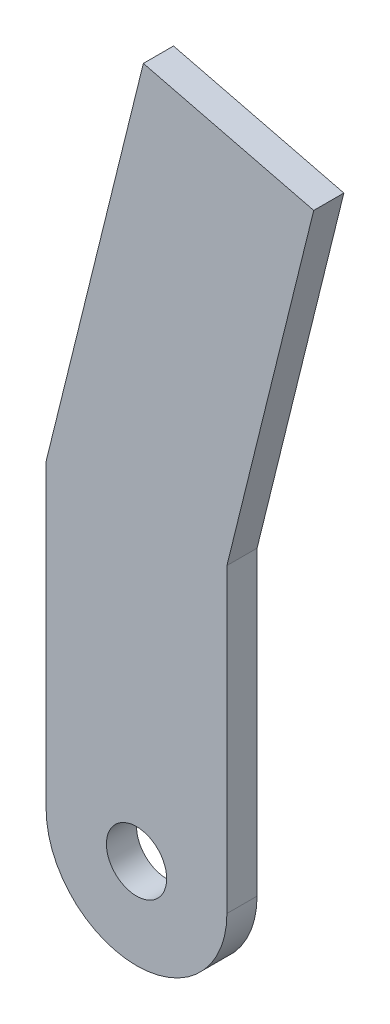
SolidWorks part; units mm, degrees
ref_plane "Front Plane" through (0, 0, 0) normal (0, 0, 1) x (1, 0, 0)
ref_plane "Top Plane" through (0, 0, 0) normal (0, 1, 0) x (1, 0, 0)
ref_plane "Right Plane" through (0, 0, 0) normal (1, 0, 0) x (0, 0, -1)
sketch "Sketch1" plane through (0, 0, 0) normal (0, 0, 1) x (1, 0, 0)
  line L0 (-15, 50) -> (1.134, 115.2369)
  line L2 (-15, 0) -> (-15, 50)
  line L4 (15, 0) -> (15, 50)
  line L5 (1.134, 115.2369) -> (29.4048, 108.2452)
  line L6 (29.4048, 108.2452) -> (15, 50)
  arc A0 (-15, 0) -> (15, 0) centre (0, 0) ccw
  circle A1 centre (0, 0) radius 5
  dimension "D1" = 10
  dimension "D2" = 30
  dimension "D3" = 30
  dimension "D4" = 50
  dimension "D5" = 60
extrude "Boss-Extrude1" add sketch "Sketch1" along normal blind 5 contours A0 L4 L6 L5 L0 L2 | A1
